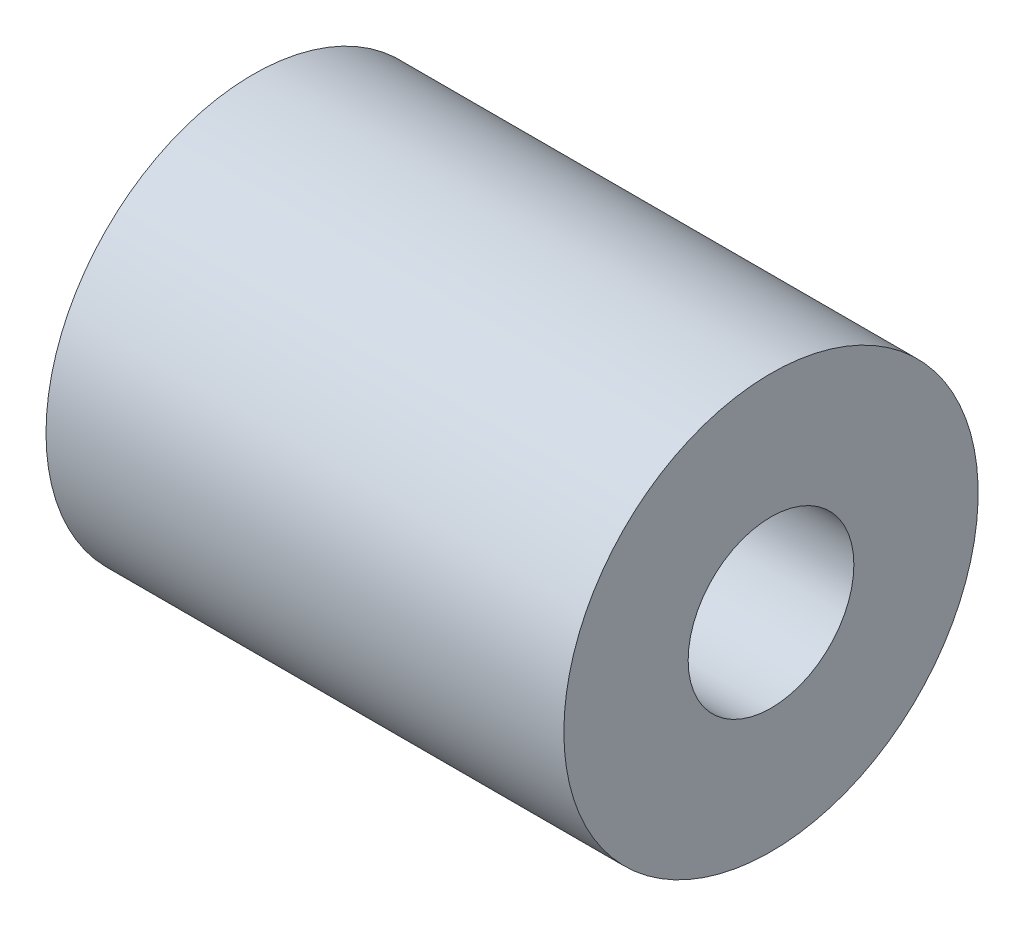
SolidWorks part; units mm, degrees
material "1.4511 (X3CrNb17)"
ref_plane "前视基准面" through (0, 0, 0) normal (0, 0, 1) x (1, 0, 0)
ref_plane "上视基准面" through (0, 0, 0) normal (0, 1, 0) x (1, 0, 0)
ref_plane "右视基准面" through (0, 0, 0) normal (1, 0, 0) x (0, 0, -1)
sketch "草图1" plane through (0, 0, 0) normal (0, 0, 1) x (1, 0, 0)
  line L0 (-12.5, 0) -> (12.5, 0)
  line L1 (-12.5, 10) -> (12.5, 10)
  line L2 (-12.5, 10) -> (-12.5, 0)
  line L4 (12.5, 10) -> (12.5, 0)
  point P0 (0, 0)
  point P9 (0, 0)
  dimension "D1" = 25
  dimension "D2" = 10
revolve "旋转1" add sketch "草图1" angle 360 about L0
sketch "草图2" plane through (12.5, 0, 0) normal (1, 0, 0) x (0, 0, -1)
  circle A0 centre (0, 0) radius 4
  dimension "D1" = 8
extrude "切除-拉伸1" cut sketch "草图2" against normal blind 8.5
mirror "镜向1" about plane through (0, 0, 0) normal (1, 0, 0) of "切除-拉伸1"
